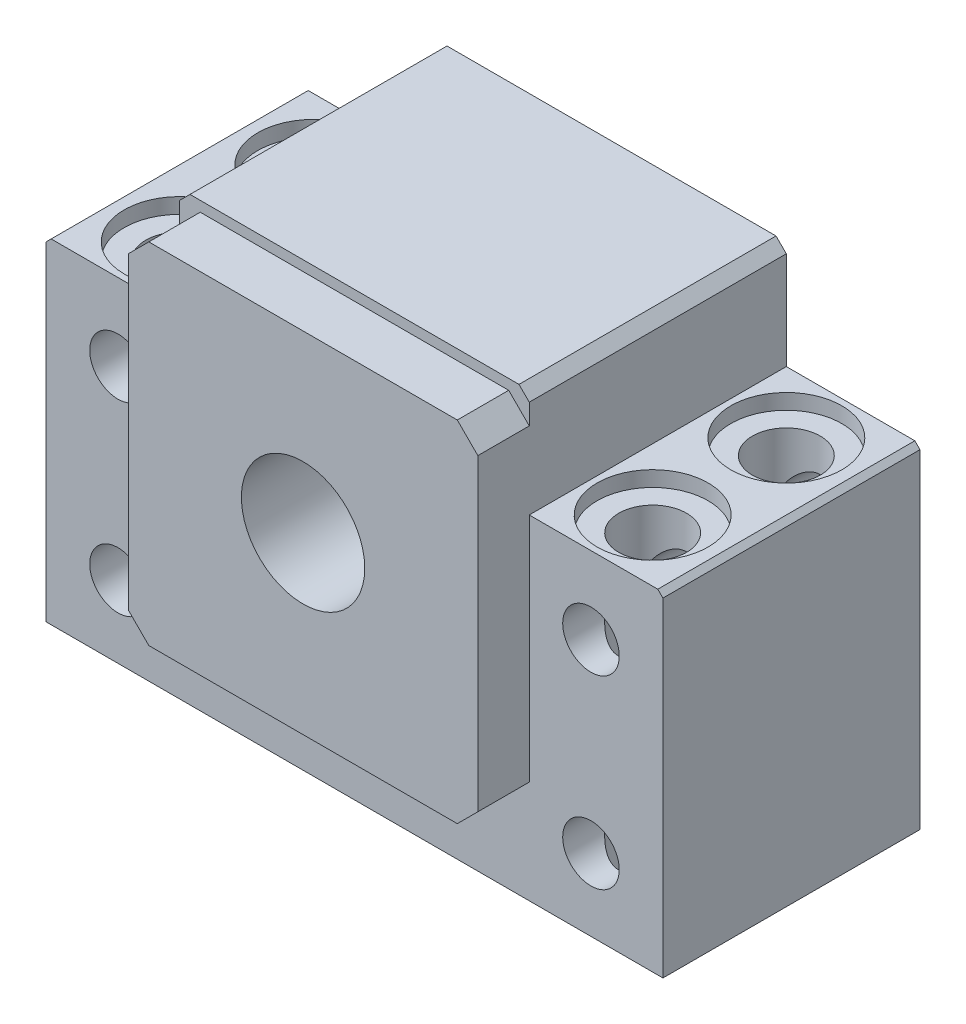
SolidWorks part; units mm, degrees
material "6061-T6 (SS)"
ref_plane "Спереди" through (0, 0, 0) normal (0, 0, 1) x (1, 0, 0)
ref_plane "Сверху" through (0, 0, 0) normal (0, 1, 0) x (1, 0, 0)
ref_plane "Справа" through (0, 0, 0) normal (1, 0, 0) x (0, 0, -1)
sketch "Эскиз1" plane through (0, 0, 0) normal (0, 0, 1) x (1, 0, 0)
  line L0 (0, -25) -> (0, 14) construction
  line L1 (-30, 7) -> (-30, -25)
  line L2 (-30, -25) -> (30, -25)
  line L3 (30, -25) -> (30, 7)
  line L4 (29.5, 7.5) -> (17, 7.5)
  line L5 (17, 7.5) -> (17, 17)
  line L6 (-17, 7.5) -> (-17, 17)
  line L7 (-29.5, 7.5) -> (-30, 7)
  line L8 (-29.5, 7.5) -> (-17, 7.5)
  line L9 (-23, -2.75) -> (-23, 2.75) construction
  line L10 (-16, 18) -> (16, 18)
  line L11 (23, -15.25) -> (23, -20.75) construction
  line L12 (-20.25, -18) -> (-25.75, -18) construction
  line L13 (20.25, -18) -> (25.75, -18) construction
  line L14 (-23, -15.25) -> (-23, -20.75) construction
  line L15 (23, -2.75) -> (23, 2.75) construction
  line L16 (30, 7) -> (29.5, 7.5)
  line L17 (-30, 0) -> (30, 0) construction
  line L18 (-17, 17) -> (-16, 18)
  line L19 (17, 17) -> (16, 18)
  circle A0 centre (0, 0) radius 6
  circle A1 centre (-23, 0) radius 2.75
  circle A2 centre (-23, -18) radius 2.75
  circle A3 centre (23, -18) radius 2.75
  circle A4 centre (23, 0) radius 2.75
  point P6 (30, 7.5)
  point P8 (17, 18)
  point P13 (-17, 18)
  point P16 (-30, 7.5)
  dimension "D1" = 60
  dimension "D9" = 5.5
  dimension "D2" = 46
  dimension "D3" = 30
  dimension "D4" = 25
  dimension "D5" = 32.5
  dimension "D6" = 43
  dimension "D7" = 34
  dimension "D8" = 18
extrude "Бобышка-Вытянуть1" add sketch "Эскиз1" against normal blind 25
sketch "Эскиз2" plane through (0, 0, 0) normal (0, 0, 1) x (1, 0, 0)
  line L0 (-17, 15) -> (-15, 17)
  line L1 (-15, 17) -> (15, 17)
  line L4 (17, 15) -> (17, -15)
  line L5 (15, -17) -> (-15, -17)
  line L6 (-17, -15) -> (-17, 15)
  line L7 (15, 17) -> (17, 15)
  line L8 (-15, -17) -> (-17, -15)
  line L9 (17, -15) -> (15, -17)
  circle A0 centre (0, 0) radius 6
  point P4 (-17, 17)
  point P6 (17, 17)
  point P11 (-17, -17)
  point P12 (17, -17)
extrude "Бобышка-Вытянуть2" add sketch "Эскиз2" along normal blind 5
sketch "Эскиз3" plane through (0, 0, 0) normal (0, 1, 0) x (1, 0, 0)
  line L0 (23, 25) -> (23, 0) construction
  line L1 (0, 25) -> (0, -5) construction
  line L2 (-17, 25) -> (-29.5, 25) construction
  line L3 (30, 25) -> (30, 0) construction
  line L4 (-30, 19) -> (30, 19) construction
  line L8 (-30, 6) -> (30, 6) construction
  line L10 (-23, 25) -> (-23, 0) construction
  circle A0 centre (-23, 19) radius 3.3
  circle A1 centre (-23, 6) radius 3.3
  circle A2 centre (23, 6) radius 3.3
  circle A3 centre (23, 19) radius 3.3
  point P22 (23, 11.5348)
  dimension "D1" = 6
  dimension "D2" = 13
  dimension "D3" = 46
  dimension "D4" = 7
extrude "Вырез-Вытянуть1" cut sketch "Эскиз3" against normal through all from offset 7.5
sketch "Эскиз4" plane through (0, 0, 0) normal (0, 1, 0) x (1, 0, 0)
  circle A0 centre (-23, 19) radius 5.4
  circle A1 centre (-23, 6) radius 5.4
  circle A2 centre (23, 6) radius 5.4
  circle A3 centre (23, 19) radius 5.4
extrude "Вырез-Вытянуть2" cut sketch "Эскиз4" against normal blind 1.5 from offset 7.5
